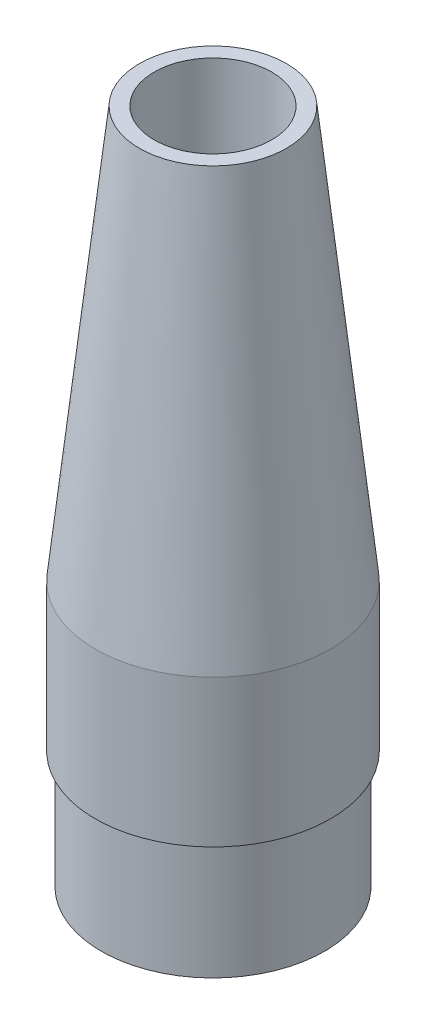
SolidWorks part; units mm, degrees
ref_plane "정면" through (0, 0, 0) normal (0, 0, 1) x (1, 0, 0)
ref_plane "윗면" through (0, 0, 0) normal (0, 1, 0) x (1, 0, 0)
ref_plane "우측면" through (0, 0, 0) normal (1, 0, 0) x (0, 0, -1)
sketch "스케치1" plane through (0, 0, 0) normal (0, 0, 1) x (1, 0, 0)
  line L0 (10, 0) -> (19, 0)
  line L1 (19, 0) -> (19, 20)
  line L3 (12.5, 115) -> (10, 115)
  line L4 (10, 115) -> (10, 85)
  line L5 (10, 85) -> (5, 85)
  line L6 (5, 85) -> (5, 80)
  line L7 (7.7827, 75.8138) -> (10, 70.5532)
  line L8 (10, 70.5532) -> (10, 0)
  line L9 (5, 80) -> (7.7827, 80)
  line L10 (7.7827, 80) -> (7.7827, 75.8138)
  line L11 (0, 0) -> (0, 169.6948) construction
  line L12 (19, 20) -> (20, 20)
  line L13 (20, 20) -> (20, 45)
  line L14 (20, 45) -> (12.5, 115)
  dimension "D1" = 80
  dimension "D2" = 5
  dimension "D3" = 10
  dimension "D4" = 19
  dimension "D5" = 10
  dimension "D6" = 20
  dimension "D7" = 2.5
  dimension "D8" = 30
  dimension "D9" = 20
  dimension "D10" = 20
  dimension "D11" = 25
  dimension "D12" = 70.5532
revolve "회전1" add sketch "스케치1" angle 360 about L11
